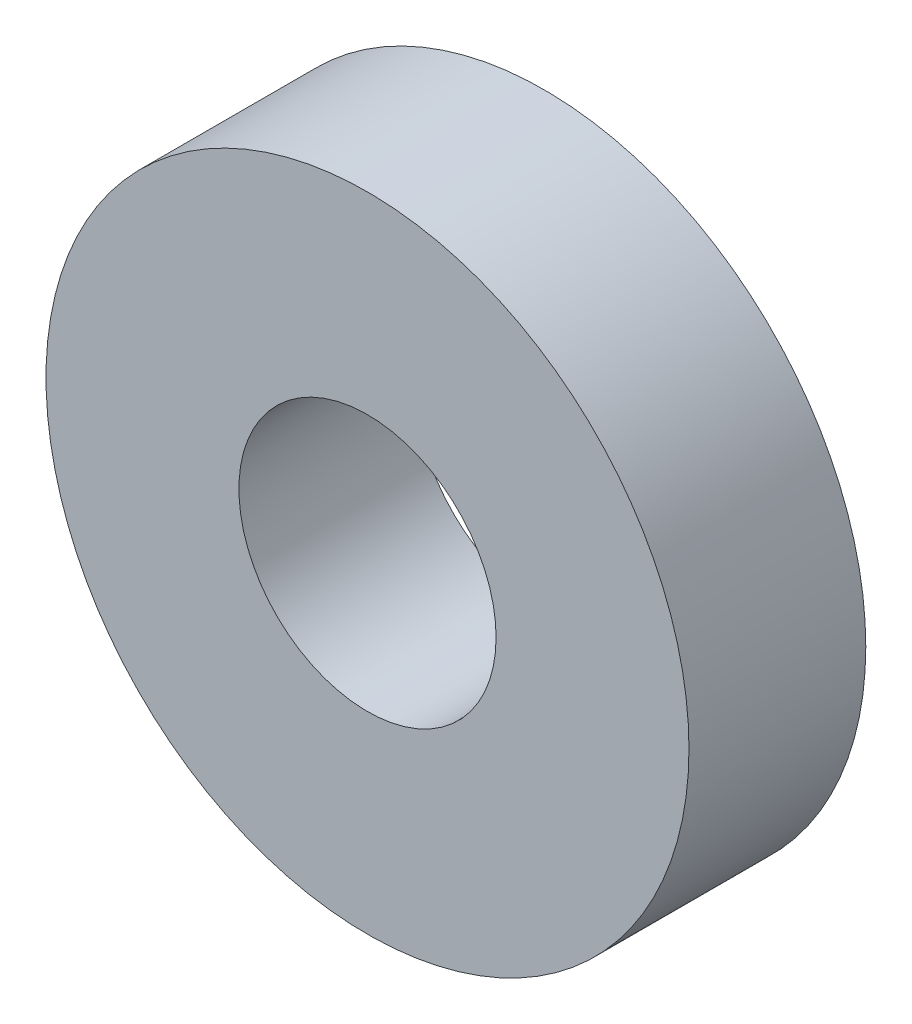
SolidWorks part; units mm, degrees
ref_plane "Front Plane" through (0, 0, 0) normal (0, 0, 1) x (1, 0, 0)
ref_plane "Top Plane" through (0, 0, 0) normal (0, 1, 0) x (1, 0, 0)
ref_plane "Right Plane" through (0, 0, 0) normal (1, 0, 0) x (0, 0, -1)
sketch "Sketch1" plane through (0, 0, 0) normal (0, 0, 1) x (1, 0, 0)
  circle A0 centre (0, 0) radius 4
  circle A1 centre (0, 0) radius 10
  dimension "D1" = 20
  dimension "D2" = 8
extrude "Boss-Extrude1" add sketch "Sketch1" along normal blind 5.5
